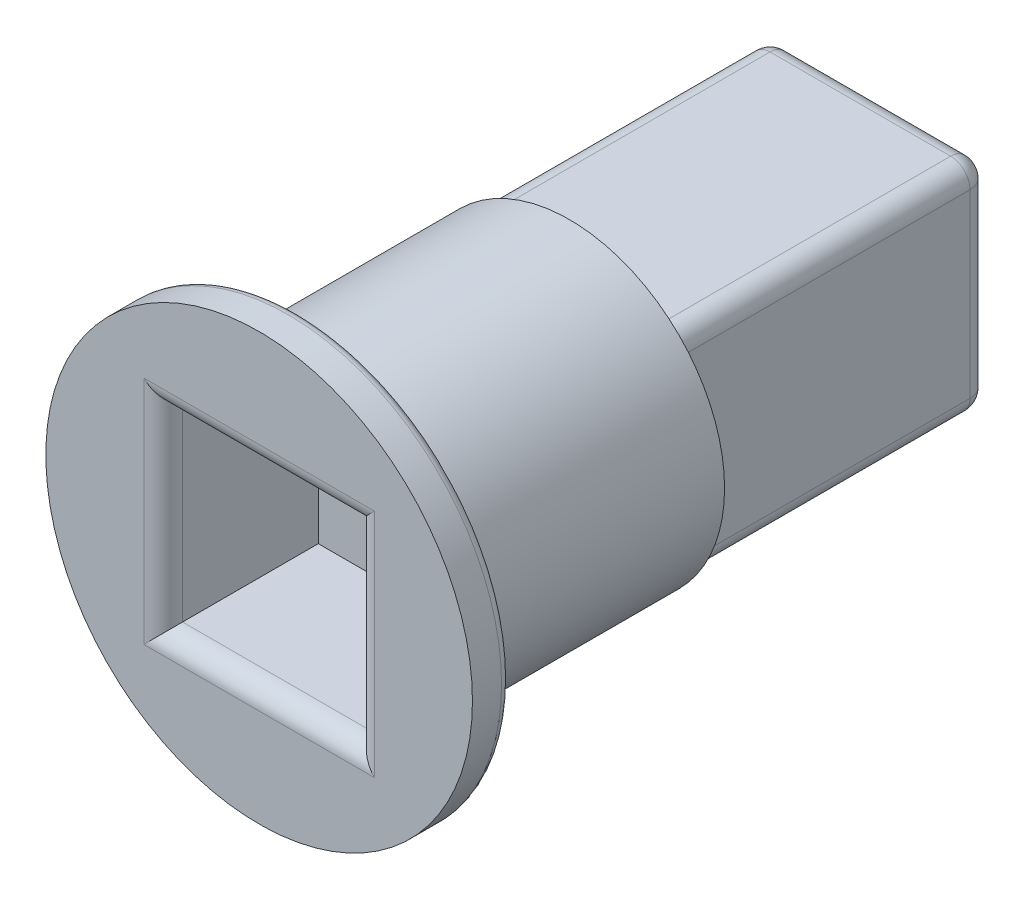
SolidWorks part; units mm, degrees
material "ABS"
ref_plane "Plan de face" through (0, 0, 0) normal (0, 0, 1) x (1, 0, 0)
ref_plane "Plan de dessus" through (0, 0, 0) normal (0, 1, 0) x (1, 0, 0)
ref_plane "Plan de droite" through (0, 0, 0) normal (1, 0, 0) x (0, 0, -1)
sketch "Esquisse1" plane through (0, 0, 0) normal (0, 0, 1) x (1, 0, 0)
  circle A0 centre (0, 0) radius 4
  dimension "D1" = 8
extrude "Extrusion1" add sketch "Esquisse1" against normal blind 7
sketch "Esquisse3" plane through (0, 0, -7) normal (0, 0, -1) x (-1, 0, 0)
  line L0 (-2.8284, 2.8284) -> (2.8284, -2.8284) construction
  line L1 (-2.8284, 2.8284) -> (2.8284, 2.8284)
  line L2 (-2.8284, 2.8284) -> (-2.8284, -2.8284)
  line L3 (-2.8284, -2.8284) -> (2.8284, -2.8284)
  line L4 (2.8284, 2.8284) -> (2.8284, -2.8284)
  line L5 (-2.8284, -2.8284) -> (2.8284, 2.8284) construction
  circle A2 centre (0, 0) radius 4 construction
  point P4 (0, 0)
  point P5 (0, 0)
extrude "Extrusion3" add sketch "Esquisse3" along normal blind 8
fillet "Congé4" radius 0.5 8 edges at (-2.8284, -2.8284, -11) (2.8284, -2.8284, -11) (-2.8284, 2.8284, -11) (2.8284, 2.8284, -11) (0, -2.8284, -15) (-2.8284, 0, -15) (0, 2.8284, -15) (2.8284, 0, -15)
sketch "Esquisse7" plane through (0, 0, 0) normal (0, 0, 1) x (1, 0, 0)
  circle A0 centre (0, 0) radius 5.5
  dimension "D1" = 11
extrude "Extrusion6" add sketch "Esquisse7" along normal blind 1
sketch "Esquisse8" plane through (0, 0, 1) normal (0, 0, 1) x (1, 0, 0)
  circle A0 centre (0, 0) radius 1.5
  dimension "D1" = 3
extrude "Extrusion7" cut sketch "Esquisse8" against normal through all
sketch "Esquisse9" plane through (0, 0, 1) normal (0, 0, 1) x (1, 0, 0)
  line L0 (-2.4749, 2.4749) -> (2.4749, -2.4749) construction
  line L1 (-2.4749, 2.4749) -> (2.4749, 2.4749)
  line L2 (-2.4749, 2.4749) -> (-2.4749, -2.4749)
  line L3 (-2.4749, -2.4749) -> (2.4749, -2.4749)
  line L4 (2.4749, 2.4749) -> (2.4749, -2.4749)
  line L5 (2.4749, 2.4749) -> (-2.4749, -2.4749) construction
  circle A0 centre (0, 0) radius 3.5 construction
  point P7 (0, 0)
  dimension "D1" = 7
extrude "Extrusion8" cut sketch "Esquisse9" against normal blind 4
fillet "Congé5" radius 0.25 1 edges at (5.5, 0, 0)
fillet "Congé6" radius 0.5 4 edges at (-2.4749, 0, 1) (0, -2.4749, 1) (2.4749, 0, 1) (0, 2.4749, 1)
